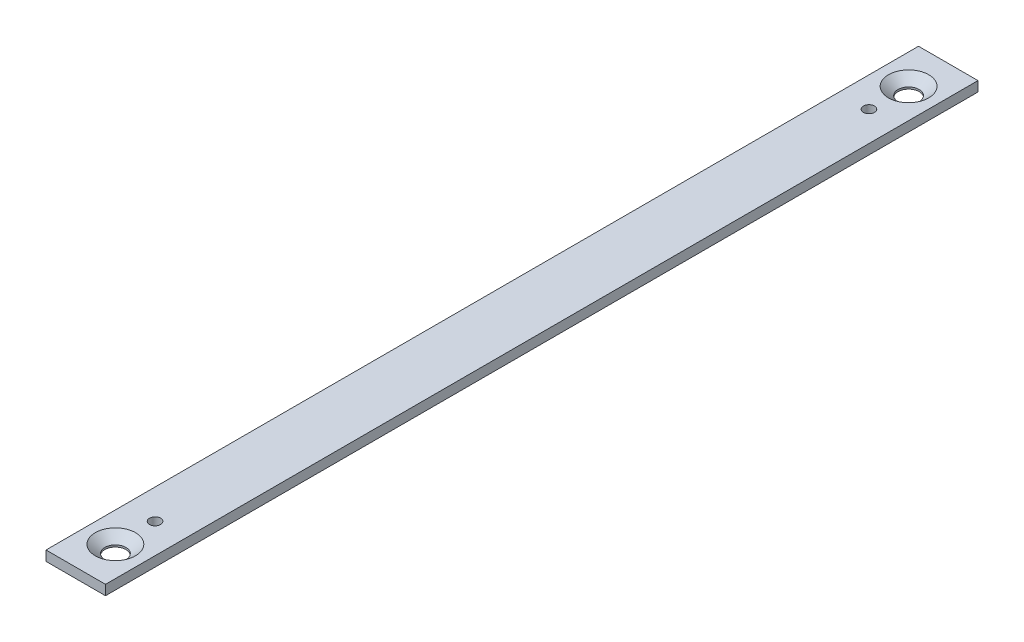
SolidWorks part; units mm, degrees
ref_plane "Front Plane" through (0, 0, 0) normal (0, 0, 1) x (1, 0, 0)
ref_plane "Top Plane" through (0, 0, 0) normal (0, 1, 0) x (1, 0, 0)
ref_plane "Right Plane" through (0, 0, 0) normal (1, 0, 0) x (0, 0, -1)
sketch "Sketch1" plane through (0, 0, 0) normal (0, 1, 0) x (1, 0, 0)
  line L0 (0, -127) -> (0, 127) construction
  line L1 (-9.525, -139.7) -> (9.525, -139.7)
  line L2 (-9.525, -139.7) -> (-9.525, 139.7)
  line L3 (-9.525, 139.7) -> (9.525, 139.7)
  line L4 (9.525, -139.7) -> (9.525, 139.7)
  line L5 (-9.525, -139.7) -> (9.525, 139.7) construction
  line L6 (-9.525, 139.7) -> (9.525, -139.7) construction
  line L7 (0, -114.3) -> (0, 114.3) construction
  circle A2 centre (0, 114.3) radius 1.778
  circle A3 centre (0, -114.3) radius 1.778
  point P0 (0, 0)
  point P9 (0, 0)
  point P10 (0, 0)
  point P13 (0, 0)
  dimension "D2" = 12.7
  dimension "D3" = 3.556
  dimension "D1" = 279.4
  dimension "D4" = 19.05
  dimension "D5" = 228.6
extrude "Boss-Extrude1" add sketch "Sketch1" against normal blind 3.175
hole_wizard "CSK for 1/4 Flat Head Machine Screw (100)1" positions "Sketch2" profile "Sketch3" countersink size "1/4" standard "ANSI Inch" end condition through all
sketch "Sketch2" plane through (0, 0, 0) normal (0, 1, 0) x (1, 0, 0)
  point P0 (0, -127)
  point P3 (0, 127)
sketch "Sketch3" plane through (0, 0, 127) normal (1, 0, 0) x (0, 0, 1)
  line L0 (0, 0) -> (0, 3.175)
  line L1 (0, 3.175) -> (3.3782, 3.175)
  line L2 (3.3782, 3.175) -> (3.3782, 2.5682)
  line L3 (3.3782, 2.5682) -> (6.4389, 0)
  line L5 (6.4389, 0) -> (0, 0)
  line L6 (-3.3782, 2.5682) -> (-6.4389, 0) construction
  line L11 (0, -6.35) -> (0, 107.95) construction
  dimension "Thru Hole Dia." = 6.7564
  dimension "Thru Hole Depth" = 3.175
  dimension "Near C'Sink Dia." = 12.8778
  dimension "Near C'Sink Angle" = 100
